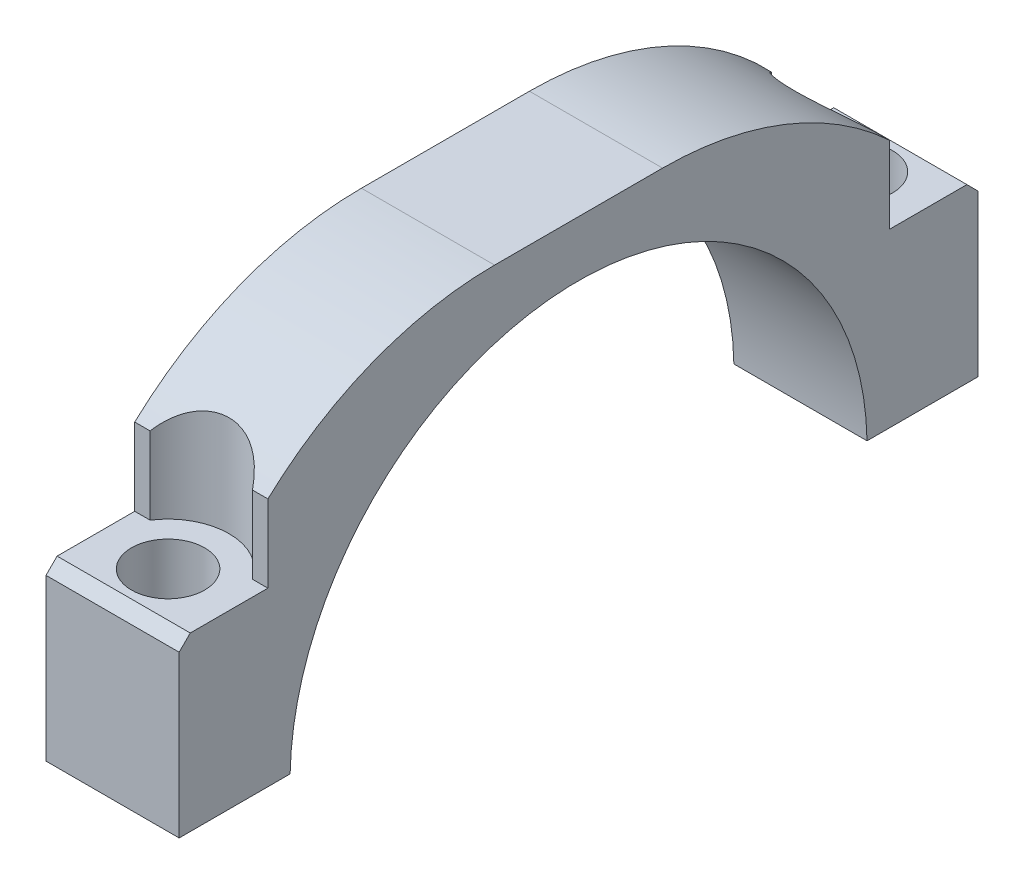
SolidWorks part; units mm, degrees
material "2014 Alloy"
ref_plane "Front Plane" through (0, 0, 0) normal (0, 0, 1) x (1, 0, 0)
ref_plane "Top Plane" through (0, 0, 0) normal (0, 1, 0) x (1, 0, 0)
ref_plane "Right Plane" through (0, 0, 0) normal (1, 0, 0) x (0, 0, -1)
sketch "Sketch1" plane through (0, 0, 0) normal (1, 0, 0) x (0, 0, -1)
  line L0 (-35.9952, 0) -> (35.9952, 0)
  line L1 (35.9952, 0) -> (35.9952, -30.5)
  line L2 (35.9952, -30.5) -> (25.9952, -30.5)
  line L3 (0, 0) -> (0, -31) construction
  line L4 (-35.9952, -30.5) -> (-25.9952, -30.5)
  line L5 (-35.9952, 0) -> (-35.9952, -30.5)
  arc A0 (25.9952, -30.5) -> (-25.9952, -30.5) centre (0, -31) ccw
  dimension "D1" = 30.5
  dimension "D3" = 26
  dimension "D2" = 10
  dimension "D4" = 0.5
extrude "Boss-Extrude1" add sketch "Sketch1" along normal blind 12
chamfer "Chamfer1" distance 16 angle 45 2 edges at (6, 0, -35.9952) (6, 0, 35.9952)
fillet "Fillet1" radius 30 2 edges at (6, 0, -19.9952) (6, 0, 19.9952)
hole_wizard "M6 Clearance Hole1" positions "Sketch3" profile "Sketch2" hole size "M6" standard "ISO" end condition through all
sketch "Sketch3" plane through (0, -30.5, 0) normal (0, -1, 0) x (-1, 0, 0)
  line L3 (-6, -25.9952) -> (-6, 25.9952) construction
  line L4 (-12, 25.9952) -> (0, 25.9952) construction
  line L5 (-6, 25.9952) -> (-6, 35.9952) construction
  line L6 (-12, 35.9952) -> (0, 35.9952) construction
  line L9 (-6, -25.9952) -> (-6, -35.9952) construction
  line L10 (-12, -35.9952) -> (0, -35.9952) construction
  line L12 (-12, -25.9952) -> (0, -25.9952) construction
  point P0 (-6, -30.9952)
  point P2 (-6, 30.9952)
sketch "Sketch2" plane through (6, -30.5, 30.9952) normal (1, 0, 0) x (0, 0, -1)
  line L0 (0, 0) -> (0, 30.5)
  line L1 (0, 30.5) -> (3.3, 30.5)
  line L2 (3.3, 30.5) -> (3.3, 0)
  line L5 (3.3, 0) -> (0, 0)
  line L11 (0, -6.35) -> (0, 107.95) construction
  dimension "Thru Hole Dia." = 6.6
  dimension "Thru Hole Depth" = 30.5
sketch "Sketch4" plane through (0, 0, 0) normal (0, 1, 0) x (1, 0, 0)
  circle A0 centre (6, -30.9952) radius 5.5
  circle A1 centre (6, 30.9952) radius 5.5
  dimension "D1" = 11
extrude "Cut-Extrude1" cut sketch "Sketch4" against normal blind 15
sketch "Sketch5" plane through (0, 0, 0) normal (0, 1, 0) x (1, 0, 0)
  line L0 (-5.937, -40.9469) -> (-5.937, -28)
  line L1 (-5.937, -40.9469) -> (17.937, -40.9469)
  line L2 (-5.937, -28) -> (17.937, -28)
  line L3 (17.937, -40.9469) -> (17.937, -28)
  line L4 (-5.937, -40.9469) -> (17.937, -28) construction
  line L5 (-5.937, -28) -> (17.937, -40.9469) construction
  line L8 (0, 0) -> (16.1654, 0) construction
  line L9 (-5.937, 28) -> (17.937, 40.9469) construction
  line L10 (-5.937, 40.9469) -> (17.937, 28) construction
  line L11 (17.937, 40.9469) -> (17.937, 28)
  line L12 (-5.937, 28) -> (17.937, 28)
  line L13 (-5.937, 40.9469) -> (17.937, 40.9469)
  line L14 (-5.937, 40.9469) -> (-5.937, 28)
  point P3 (6, -34.4734)
  point P9 (6, 34.4734)
  dimension "D1" = 28
extrude "Cut-Extrude2" cut sketch "Sketch5" against normal blind 15
sketch "Sketch8" [suppressed] plane through (12, 0, 0) normal (1, 0, 0) x (0, 0, -1)
  line L18 (-29, -7.6013) -> (-29, -15)
  line L19 (-29, -15) -> (-36.9952, -15)
  line L20 (-36.9952, -15) -> (-36.9952, -31.5)
  line L21 (-36.9952, -31.5) -> (-24.995, -31.5)
  line L22 (24.995, -31.5) -> (36.9952, -31.5)
  line L23 (36.9952, -31.5) -> (36.9952, -15)
  line L24 (36.9952, -15) -> (29, -15)
  line L25 (29, -15) -> (29, -7.6013)
  line L26 (7.5688, 1) -> (-7.5688, 1)
  line L27 (-29, -7.6013) -> (-29, -15)
  line L28 (-29, -15) -> (-36.9952, -15)
  line L29 (-36.9952, -15) -> (-36.9952, -31.5)
  line L30 (-36.9952, -31.5) -> (-24.995, -31.5)
  line L31 (24.995, -31.5) -> (36.9952, -31.5)
  line L32 (36.9952, -31.5) -> (36.9952, -15)
  line L33 (36.9952, -15) -> (29, -15)
  line L34 (29, -15) -> (29, -7.6013)
  line L35 (7.5688, 1) -> (-7.5688, 1)
  arc A8 (24.995, -31.5) -> (-24.995, -31.5) centre (0, -31) ccw
  arc A9 (29, -7.6013) -> (7.5688, 1) centre (7.5688, -30) ccw
  arc A10 (-7.5688, 1) -> (-29, -7.6013) centre (-7.5688, -30) ccw
  arc A11 (24.995, -31.5) -> (-24.995, -31.5) centre (0, -31) ccw
  arc A12 (29, -7.6013) -> (7.5688, 1) centre (7.5688, -30) ccw
  arc A13 (-7.5688, 1) -> (-29, -7.6013) centre (-7.5688, -30) ccw
  dimension "D1" = 1
extrude "Boss-Extrude4" [suppressed] add sketch "Sketch8" against normal blind 15
